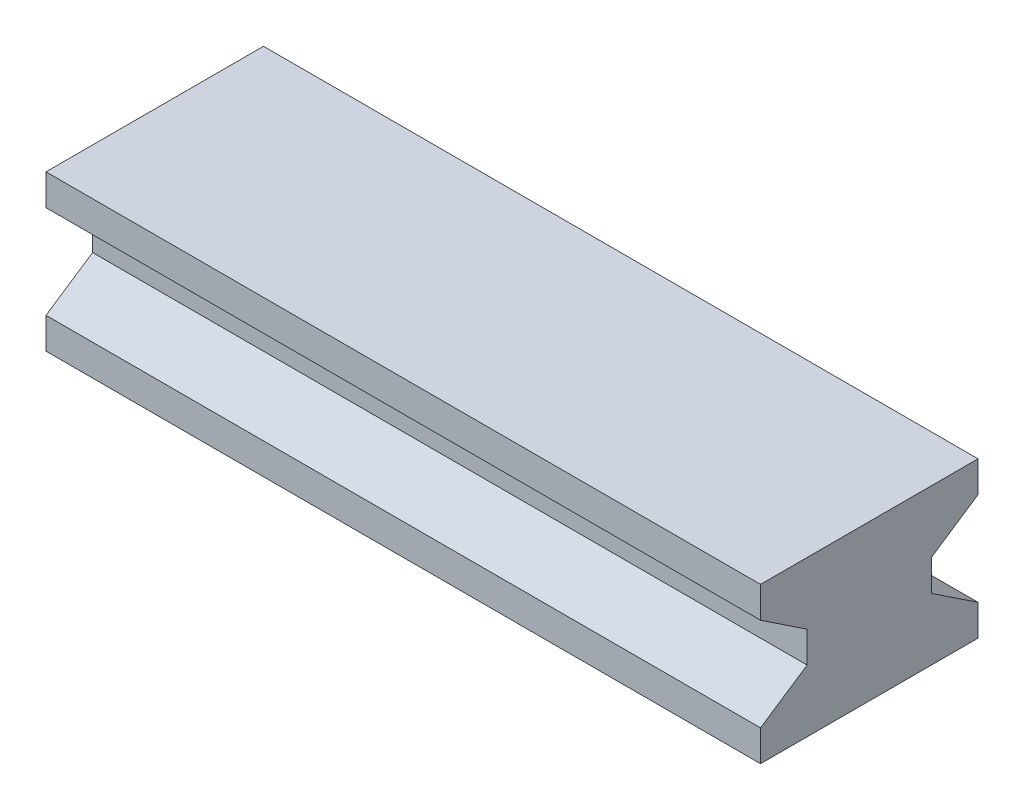
SolidWorks part; units mm, degrees
material "Aleación 1060"
ref_plane "Alzado" through (0, 0, 0) normal (0, 0, 1) x (1, 0, 0)
ref_plane "Planta" through (0, 0, 0) normal (0, 1, 0) x (1, 0, 0)
ref_plane "Vista lateral" through (0, 0, 0) normal (1, 0, 0) x (0, 0, -1)
sketch "Croquis1" plane through (0, 0, 0) normal (1, 0, 0) x (0, 0, -1)
  line L0 (-35, -15) -> (-20, -5)
  line L1 (-35, -25) -> (35, -25)
  line L2 (-35, -25) -> (-35, 25)
  line L3 (-35, 25) -> (35, 25)
  line L4 (35, -25) -> (35, 25)
  line L5 (-35, -25) -> (35, 25) construction
  line L6 (-35, 25) -> (35, -25) construction
  line L7 (-20, -5) -> (-20, 5)
  line L8 (-20, 5) -> (-35, 15)
  line L9 (20, -5) -> (35, -15)
  line L10 (20, 5) -> (20, -5)
  line L11 (35, 15) -> (20, 5)
  point P0 (0, 0)
  point P16 (0, 0)
  dimension "D1" = 70
  dimension "D2" = 50
  dimension "D3" = 10
  dimension "D4" = 10
  dimension "D5" = 20
  dimension "D6" = 20
  dimension "D7" = 15
  dimension "D8" = 2
extrude "Saliente-Extruir1" add sketch "Croquis1" along normal blind 230 contours L11 L4 L3 L2 L8 L7 L0 L1 L9 L10
